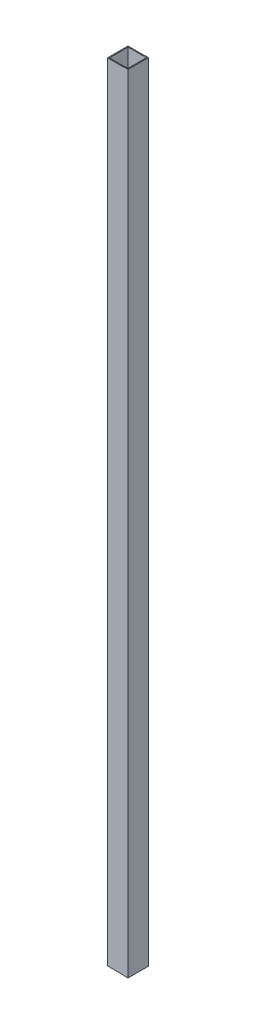
SolidWorks part; units mm, degrees
ref_plane "Front Plane" through (0, 0, 0) normal (0, 0, 1) x (1, 0, 0)
ref_plane "Top Plane" through (0, 0, 0) normal (0, 1, 0) x (1, 0, 0)
ref_plane "Right Plane" through (0, 0, 0) normal (1, 0, 0) x (0, 0, -1)
sketch "Sketch1" plane through (0, 0, 0) normal (0, 1, 0) x (1, 0, 0)
  line L0 (0, 0) -> (0, 50)
  line L1 (0, 50) -> (50, 50)
  line L2 (50, 50) -> (50, 0)
  line L3 (50, 0) -> (0, 0)
  line L4 (2.2, 47.8) -> (47.8, 47.8)
  line L5 (47.8, 47.8) -> (47.8, 2.2)
  line L6 (47.8, 2.2) -> (2.2, 2.2)
  line L7 (2.2, 2.2) -> (2.2, 47.8)
  dimension "D1" = 50
  dimension "D2" = 50
  dimension "D3" = 2.2
extrude "Boss-Extrude1" add sketch "Sketch1" along normal blind 1923
sketch "Sketch2" plane through (0, 0, 0) normal (0, 0, 1) x (1, 0, 0)
  line L0 (0, 0) -> (0, 0.5)
  line L1 (0, 1923) -> (0, 0) construction
  line L2 (0, 0.5) -> (40, 0.5)
  line L3 (40, 0.5) -> (40, 0)
  line L5 (40, 0) -> (0, 0)
  line L6 (0, 1923) -> (40, 1923)
  line L7 (0, 1923) -> (50, 1923) construction
  line L8 (40, 1923) -> (40, 1922.5)
  line L9 (40, 1922.5) -> (0, 1922.5)
  line L10 (0, 1922.5) -> (0, 1923)
  dimension "D1" = 0.5
  dimension "D2" = 40
  dimension "D3" = 0.5
  dimension "D4" = 40
extrude "Cut-Extrude2" cut sketch "Sketch2" against normal blind 50
equation "\"SquareTube_length\"=1923.0"
equation "\"D1@Boss-Extrude1\"=\"SquareTube_length\""
equation "\"SquareTube_inBack1_cutDepth50_R\"=50"
equation "\"D1@Sketch2\" = \"SquareTube_inBack8_cutDepth50_R\""
equation "\"SquareTube_inBack1_cutDepth50_L\"=50"
equation "\"D3@Sketch2\" = \"SquareTube_inBack8_cutDepth50_L\""
equation "\"CarBeamWidth\"=700.0"
equation "\"MetalSheet_3mm_length\"=5030.0"
equation "\"MetalSheet_3mm_width\"=1923.0"
equation "\"MetalSheet_3mm_FloorCut_L_length\"=1764.0"
equation "\"MetalSheet_3mm_FloorCut_L_disdance\"=1665.0"
equation "\"MetalSheet_3mm_FloorCut_R_length\"=1764.0"
equation "\"MetalSheet_3mm_FloorCut_R_disdance\"=1665.0"
equation "\"indoorHeight\"=1940.0"
equation "\"x\"=66.0"
equation "\"da\"=62.0"
equation "\"SquareTube_wheel_length\"= 750"
equation "\"channelSteel_length\"=5030.0"
equation "\"SquareTube_inFront1_cutDepth50_R\"=0.5"
equation "\"SquareTube_inFront1_cutDepth50_L\"=0.5"
equation "\"SquareTube_inFront2_cutDepth50_R\"=0.5"
equation "\"SquareTube_inFront2_cutDepth50_L\"=0.5"
equation "\"SquareTube_inFront3_cutDepth50_R\"=0.5"
equation "\"SquareTube_inFront3_cutDepth50_L\"=0.5"
equation "\"SquareTube_inFront4_cutDepth50_R\"=0.5"
equation "\"SquareTube_inFront4_cutDepth50_L\"=0.5"
equation "\"SquareTube_inFront5_cutDepth50_R\"=50"
equation "\"SquareTube_inFront5_cutDepth50_L\"=50"
equation "\"SquareTube_inFront6_cutDepth50_R\"=50"
equation "\"SquareTube_inFront6_cutDepth50_L\"=50"
equation "\"SquareTube_inFront7_cutDepth50_R\"=50"
equation "\"SquareTube_inFront7_cutDepth50_L\"=50"
equation "\"SquareTube_inFront8_cutDepth50_R\"=50"
equation "\"SquareTube_inFront8_cutDepth50_L\"=50"
equation "\"SquareTube_inFront9_cutDepth50_R\"=50"
equation "\"SquareTube_inFront9_cutDepth50_L\"=50"
equation "\"SquareTube_inFront10_cutDepth50_R\"=50"
equation "\"SquareTube_inFront10_cutDepth50_L\"=50"
equation "\"SquareTube_inBack2_cutDepth50_R\"=50"
equation "\"SquareTube_inBack2_cutDepth50_L\"=50"
equation "\"SquareTube_inBack3_cutDepth50_R\"=50"
equation "\"SquareTube_inBack3_cutDepth50_L\"=50"
equation "\"SquareTube_inBack4_cutDepth50_R\"=50"
equation "\"SquareTube_inBack4_cutDepth50_L\"=50"
equation "\"SquareTube_inBack5_cutDepth50_R\"=50"
equation "\"SquareTube_inBack5_cutDepth50_L\"=50"
equation "\"SquareTube_inBack6_cutDepth50_R\"=0.5"
equation "\"SquareTube_inBack6_cutDepth50_L\"=0.5"
equation "\"SquareTube_inFront11_cutDepth50_R\"=50"
equation "\"SquareTube_inFront11_cutDepth50_L\"=50"
equation "\"SquareTube_inFront12_cutDepth50_R\"=50"
equation "\"SquareTube_inFront12_cutDepth50_L\"=50"
equation "\"SquareTube_inFront13_cutDepth50_R\"=50"
equation "\"SquareTube_inFront13_cutDepth50_L\"=50"
equation "\"SquareTube_inFront14_cutDepth50_R\"=50"
equation "\"SquareTube_inFront14_cutDepth50_L\"=50"
equation "\"SquareTube_inBack7_cutDepth50_R\"=0.5"
equation "\"SquareTube_inBack7_cutDepth50_L\"=0.5"
equation "\"SquareTube_inBack8_cutDepth50_R\"=0.5"
equation "\"SquareTube_inBack8_cutDepth50_L\"=0.5"
